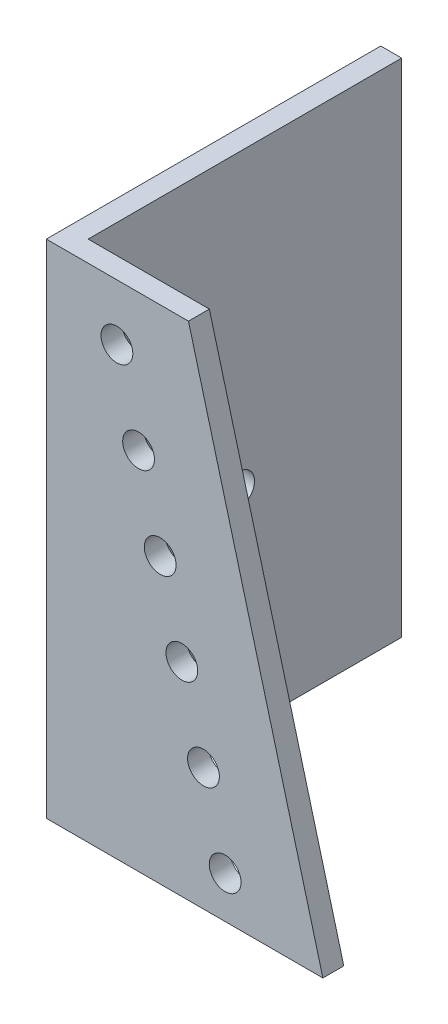
SolidWorks part; units mm, degrees
ref_plane "Front Plane" through (0, 0, 0) normal (0, 0, 1) x (1, 0, 0)
ref_plane "Top Plane" through (0, 0, 0) normal (0, 1, 0) x (1, 0, 0)
ref_plane "Right Plane" through (0, 0, 0) normal (1, 0, 0) x (0, 0, -1)
sketch "Sketch1" plane through (0, 0, 0) normal (0, 1, 0) x (1, 0, 0)
  line L0 (0, 0) -> (0, 50.8)
  line L1 (0, 50.8) -> (3.175, 50.8)
  line L2 (3.175, 50.8) -> (3.175, 3.175)
  line L3 (3.175, 3.175) -> (50.8, 3.175)
  line L4 (50.8, 3.175) -> (50.8, 0)
  line L5 (50.8, 0) -> (0, 0)
  dimension "D1" = 50.8
  dimension "D2" = 50.8
  dimension "D3" = 3.175
  dimension "D4" = 3.175
extrude "Boss-Extrude1" add sketch "Sketch1" along normal blind 76.2
sketch "Sketch2" plane through (0, 0, -3.175) normal (0, 0, -1) x (-1, 0, 0)
  line L2 (-17.2972, 43.1518) -> (-27.1582, 6.35) construction
  line L3 (-50.8, 0) -> (-3.175, 0) construction
  line L5 (-21.59, 76.2) -> (-50.8, -32.8132)
  line L6 (-50.8, 76.2) -> (-3.175, 76.2) construction
  line L7 (-50.8, 76.2) -> (-50.8, 0) construction
  line L8 (-50.8, -32.8132) -> (-50.8, 76.2)
  line L9 (-50.8, 76.2) -> (-21.59, 76.2)
  circle A0 centre (-27.1582, 6.35) radius 2.413
  circle A1 centre (-23.8712, 18.6173) radius 2.413
  circle A2 centre (-20.5842, 30.8845) radius 2.413
  circle A3 centre (-17.2972, 43.1518) radius 2.413
  circle A4 centre (-14.0102, 55.419) radius 2.413
  circle A5 centre (-10.7232, 67.6863) radius 2.413
  dimension "D1" = 12.7
  dimension "D2" = 4.826
  dimension "D3" = 12.7
  dimension "D4" = 12.7
  dimension "D6" = 12.7
  dimension "D8" = 6.35
  dimension "D5" = 75
  dimension "D7" = 3
  dimension "D9" = 29.21
sketch "Sketch3" plane through (3.175, 0, 0) normal (1, 0, 0) x (0, 0, -1)
  line L0 (13.335, 6.35) -> (13.335, 46.2046) construction
  line L1 (26.035, 6.35) -> (26.035, 46.2046) construction
  line L2 (3.175, 0) -> (50.8, 0) construction
  line L3 (3.175, 43.1518) -> (3.175, 6.35) construction
  circle A0 centre (13.335, 6.35) radius 2.413
  circle A1 centre (26.035, 6.35) radius 2.413
  circle A2 centre (13.335, 19.05) radius 2.413
  circle A3 centre (26.035, 19.05) radius 2.413
  circle A4 centre (13.335, 31.75) radius 2.413
  circle A5 centre (26.035, 31.75) radius 2.413
  point P18 (3.175, 24.7509)
  dimension "D1" = 4.826
  dimension "D2" = 4.826
  dimension "D4" = 6.35
  dimension "D5" = 6.35
  dimension "D6" = 10.16
  dimension "D7" = 22.86
  dimension "D3" = 3
extrude "Cut-Extrude1" cut sketch "Sketch2" against normal through all
extrude "Cut-Extrude2" cut sketch "Sketch3" against normal through all
